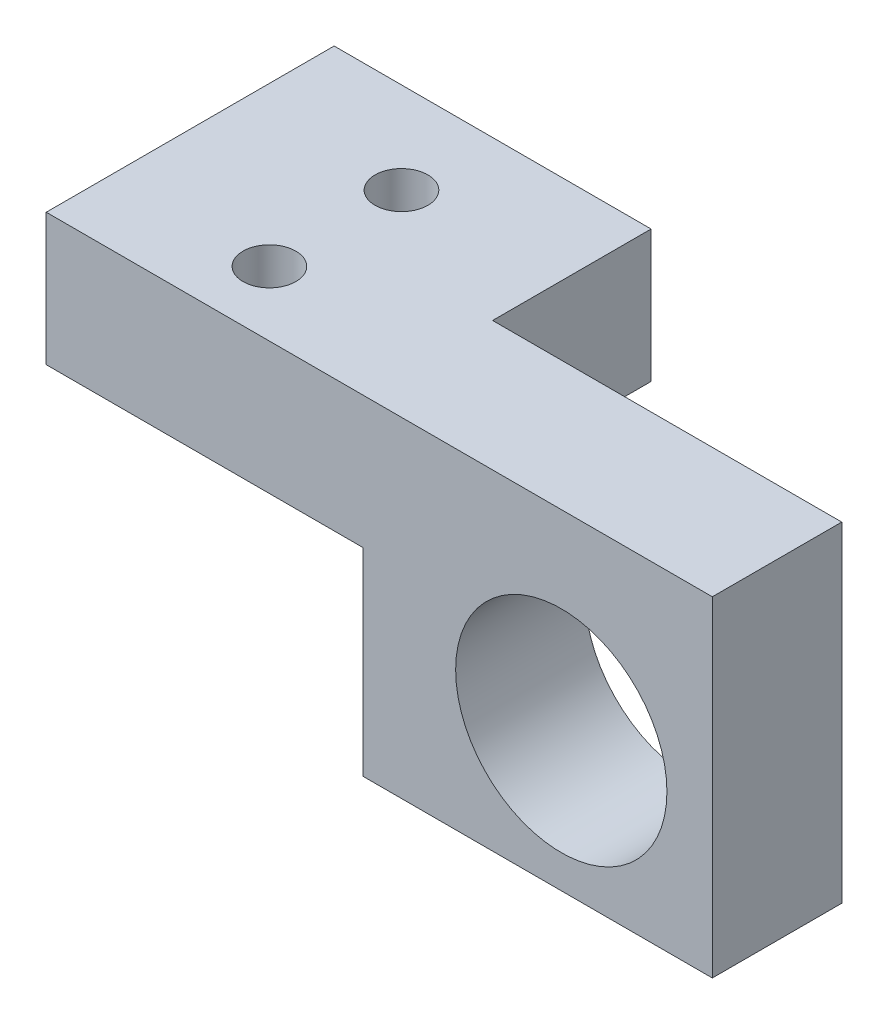
SolidWorks part; units mm, degrees
material "ABS"
ref_plane "Front Plane" through (0, 0, 0) normal (0, 0, 1) x (1, 0, 0)
ref_plane "Top Plane" through (0, 0, 0) normal (0, 1, 0) x (1, 0, 0)
ref_plane "Right Plane" through (0, 0, 0) normal (1, 0, 0) x (0, 0, -1)
sketch "Sketch1" plane through (0, 0, 0) normal (0, 0, 1) x (1, 0, 0)
  line L0 (-24, 15) -> (0, 15)
  line L1 (0, 15) -> (0, 0)
  line L2 (0, 0) -> (93, 0)
  line L3 (93, 0) -> (93, 102.7)
  line L4 (93, 102.7) -> (0, 102.7)
  line L5 (0, 102.7) -> (0, 30)
  line L6 (0, 30) -> (-24, 30)
  line L7 (-24, 30) -> (-24, 15)
  circle A0 centre (15, 10.5) radius 8
  circle A1 centre (70, 72) radius 11
  circle A2 centre (15, 10.5) radius 11
  dimension "D1" = 15
  dimension "D10" = 16
  dimension "D11" = 22
  dimension "D12" = 22
  dimension "D2" = 24
  dimension "D3" = 72.7
  dimension "D4" = 15
  dimension "D5" = 15
  dimension "D6" = 10.5
  dimension "D7" = 82.5061
  dimension "D8" = 72
  dimension "D9" = 93
extrude "Boss-Extrude1" add sketch "Sketch1" along normal blind 4.8 contours A2 L2 L3 L4 L5 L6 L7 L0 L1 A1 | L2 A2 A0
sketch "Sketch2" plane through (0, 0, 4.8) normal (0, 0, 1) x (1, 0, 0)
  line L0 (93, 0) -> (93, 102.7) construction
  line L1 (48.1786, 92.7632) -> (93, 92.7632)
  line L2 (48.1786, 92.7632) -> (48.1786, 52.666)
  line L3 (48.1786, 52.666) -> (93, 52.666)
  line L4 (93, 92.7632) -> (93, 52.666)
  line L5 (48.1786, 92.7632) -> (93, 52.666) construction
  line L6 (48.1786, 52.666) -> (93, 92.7632) construction
  circle A0 centre (70, 72) radius 11
  circle A1 centre (70, 72) radius 4.15
  point P8 (70.5893, 72.7146)
  line M4 (93, 0) -> (93, 102.7)
  circle M10 centre (70, 72) radius 11
  dimension "D1" = 22
  dimension "D2" = 8.3
extrude "Boss-Extrude2" add sketch "Sketch2" along normal blind 8.2 contours L2 L3 L1 M4 M10
sketch "Sketch3" plane through (0, 0, 4.8) normal (0, 0, 1) x (1, 0, 0)
  line L1 (-24, 15) -> (0, 15)
  line L2 (-24, 15) -> (-24, 30)
  line L3 (-24, 30) -> (0, 30)
  line L4 (0, 15) -> (0, 30)
  line L5 (-24, 15) -> (0, 30) construction
  line L6 (-24, 30) -> (0, 15) construction
  line L7 (0, 0) -> (93, 0)
  line L8 (0, 0) -> (0, 52.666)
  line L9 (0, 52.666) -> (93, 52.666)
  line L10 (93, 0) -> (93, 52.666)
  line L11 (0, 0) -> (93, 52.666) construction
  line L12 (0, 52.666) -> (93, 0) construction
  circle A0 centre (15, 10.5) radius 8
  point P4 (-12, 22.5)
  point P11 (46.5, 26.333)
  circle M1 centre (15, 10.5) radius 8
  line M6 (0, 102.7) -> (0, 30)
  line M7 (0, 30) -> (-24, 30)
  line M8 (-24, 30) -> (-24, 15)
  line M9 (-24, 15) -> (0, 15)
  line M10 (0, 15) -> (0, 0)
  line M11 (0, 0) -> (93, 0)
  line M12 (93, 0) -> (93, 52.666)
  line M13 (93, 52.666) -> (48.1786, 52.666)
extrude "Boss-Extrude3" add sketch "Sketch3" along normal blind 5 contours L4 M9 M7 M8 | L9 L4 M6 M10 M11 M12 M13 M1
sketch "Sketch4" plane through (0, 83.2317, 0) normal (0, -1, 0) x (1, 0, 0)
  line L0 (0, 9.8) -> (0, 4.8) construction
  line L1 (0, 4.8) -> (48.1786, 4.8)
  line L2 (0, 4.8) -> (0, 45.3)
  line L3 (0, 45.3) -> (48.1786, 45.3)
  line L4 (48.1786, 4.8) -> (48.1786, 45.3)
  line L5 (0, 4.8) -> (48.1786, 45.3) construction
  line L6 (0, 45.3) -> (48.1786, 4.8) construction
  line L7 (0, 4.8) -> (48.1786, 4.8) construction
  line L8 (48.1786, 13) -> (48.1786, 9.8) construction
  line L9 (0, 0) -> (93, 0) construction
  line L10 (0, 45.3) -> (-5, 45.3)
  line L11 (0, 45.3) -> (0, 0)
  line L12 (0, 0) -> (-5, 0)
  line L13 (-5, 45.3) -> (-5, 0)
  line L14 (0, 45.3) -> (-5, 0) construction
  line L15 (0, 0) -> (-5, 45.3) construction
  circle A0 centre (13.9465, 30.3) radius 6.35
  circle A1 centre (13.9465, 23.3) radius 18.5
  circle A3 centre (29.4465, 23.3) radius 2
  circle A4 centre (21.6965, 9.8766) radius 2
  circle A5 centre (6.1965, 9.8766) radius 2
  point P10 (24.0893, 25.05)
  point P30 (-2.5, 22.65)
  dimension "D1" = 12.7
  dimension "D2" = 15
  dimension "D3" = 4
  dimension "D4" = 4
  dimension "D5" = 4
  dimension "D6" = 5
  dimension "D7" = 0
extrude "Boss-Extrude4" add sketch "Sketch4" along normal blind 5
sketch "Sketch5" plane through (48.1786, 0, 0) normal (1, 0, 0) x (0, 0, -1)
  line L0 (-45.3, 83.2317) -> (-13, 92.7632)
  line L1 (-13, 92.7632) -> (-4.8, 92.7632)
  line L2 (-4.8, 92.7632) -> (-4.8, 78.2317)
  line L3 (-4.8, 78.2317) -> (-45.3, 78.2317)
  line L4 (-45.3, 78.2317) -> (-45.3, 83.2317)
extrude "Boss-Extrude5" add sketch "Sketch5" against normal blind 5
sketch "Sketch6" plane through (0, 0, 4.8) normal (0, 0, 1) x (1, 0, 0)
  line L0 (0, 78.2317) -> (0, 52.666) construction
  line L1 (0, 78.2317) -> (48.1786, 78.2317)
  line L2 (0, 78.2317) -> (0, 52.666)
  line L3 (0, 52.666) -> (48.1786, 52.666)
  line L4 (48.1786, 78.2317) -> (48.1786, 52.666)
  line L5 (0, 78.2317) -> (48.1786, 52.666) construction
  line L6 (0, 52.666) -> (48.1786, 78.2317) construction
  line L7 (0, 78.2317) -> (48.1786, 78.2317) construction
  point P4 (24.0893, 65.4489)
extrude "Boss-Extrude6" add sketch "Sketch6" along normal up to surface (5 mm away)
ref_plane "Plane1" through (3.9877, 7.5909, 34.4544) normal (0.9262, 0.2454, -0.2862) x (0.0581, -0.8429, -0.5349)
sketch "Sketch8" plane through (0, 30, 0) normal (0, 1, 0) x (1, 0, 0)
  line L0 (0, 0) -> (-24, -9.8)
  line L1 (-24, -9.8) -> (-24, 0)
  line L2 (-24, 0) -> (0, -9.8)
  circle A0 centre (-12, -4.9) radius 2
  dimension "D1" = 4
extrude "Cut-Extrude1" cut sketch "Sketch8" against normal through all contours A0
sketch "Sketch9" plane through (0, 0, 0) normal (0, 0, -1) x (-1, 0, 0)
  line L1 (0, 30) -> (-93, 30)
  line L2 (0, 30) -> (0, 102.7)
  line L3 (0, 102.7) -> (-93, 102.7)
  line L4 (-93, 30) -> (-93, 102.7)
extrude "Cut-Extrude2" cut sketch "Sketch9" against normal blind 100
sketch "Sketch10" plane through (0, 0, 9.8) normal (0, 0, 1) x (1, 0, 0)
  line L0 (93, 30) -> (-24, 30) construction
  line L1 (93, 0) -> (26.438, 0)
  line L2 (93, 0) -> (93, 30)
  line L3 (93, 30) -> (26.438, 30)
  line L4 (26.438, 0) -> (26.438, 30)
extrude "Cut-Extrude3" cut sketch "Sketch10" against normal blind 100
sketch "Sketch11" plane through (0, 0, 0) normal (0, 0, -1) x (-1, 0, 0)
  line L0 (24, 30) -> (24, 15) construction
  line L1 (0, 15) -> (24, 15)
  line L2 (0, 15) -> (0, 30)
  line L3 (0, 30) -> (24, 30)
  line L4 (24, 15) -> (24, 30)
  line L5 (-26.438, 30) -> (24, 30) construction
extrude "Boss-Extrude7" add sketch "Sketch11" along normal blind 12
sketch "Sketch13" plane through (-24, 0, 0) normal (-1, 0, 0) x (0, 0, 1)
  line L0 (9.8, 30) -> (9.8, 15) construction
  line L1 (-12, 30) -> (9.8, 30)
  line L2 (-12, 30) -> (-12, 25)
  line L3 (-12, 25) -> (9.8, 25)
  line L4 (9.8, 30) -> (9.8, 25)
  dimension "D1" = 5
extrude "Cut-Extrude4" cut sketch "Sketch13" against normal blind 200
sketch "Sketch15" plane through (0, 25, 0) normal (0, 1, 0) x (1, 0, 0)
  circle A0 centre (-12, 5.1) radius 2
  circle A1 centre (-12, -4.9) radius 2 construction
  dimension "D1" = 4
  dimension "D2" = 10
  dimension "D3" = 0
extrude "Cut-Extrude5" cut sketch "Sketch15" against normal blind 200
